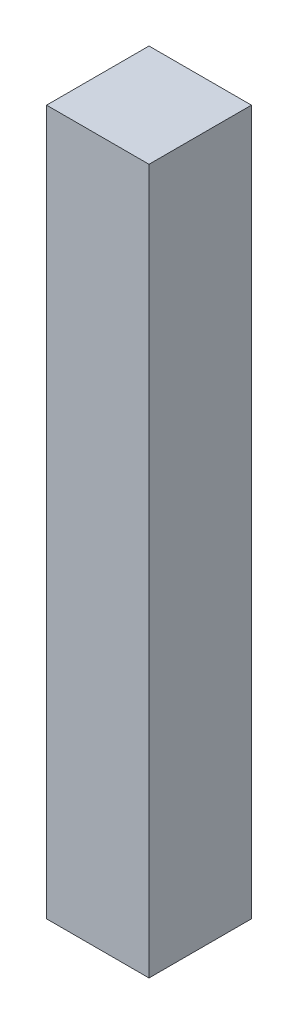
SolidWorks part; units mm, degrees
ref_plane "Front Plane" through (0, 0, 0) normal (0, 0, 1) x (1, 0, 0)
ref_plane "Top Plane" through (0, 0, 0) normal (0, 1, 0) x (1, 0, 0)
ref_plane "Right Plane" through (0, 0, 0) normal (1, 0, 0) x (0, 0, -1)
sketch "Sketch1" plane through (0, 0, 0) normal (0, 1, 0) x (1, 0, 0)
  line L1 (-7.493, -7.493) -> (7.493, -7.493)
  line L2 (-7.493, -7.493) -> (-7.493, 7.493)
  line L3 (-7.493, 7.493) -> (7.493, 7.493)
  line L4 (7.493, -7.493) -> (7.493, 7.493)
  line L5 (-7.493, -7.493) -> (7.493, 7.493) construction
  line L6 (-7.493, 7.493) -> (7.493, -7.493) construction
  point P0 (0, 0)
  dimension "D1" = 14.986
  dimension "D2" = 14.986
extrude "Boss-Extrude1" add sketch "Sketch1" along normal blind 103.1113
